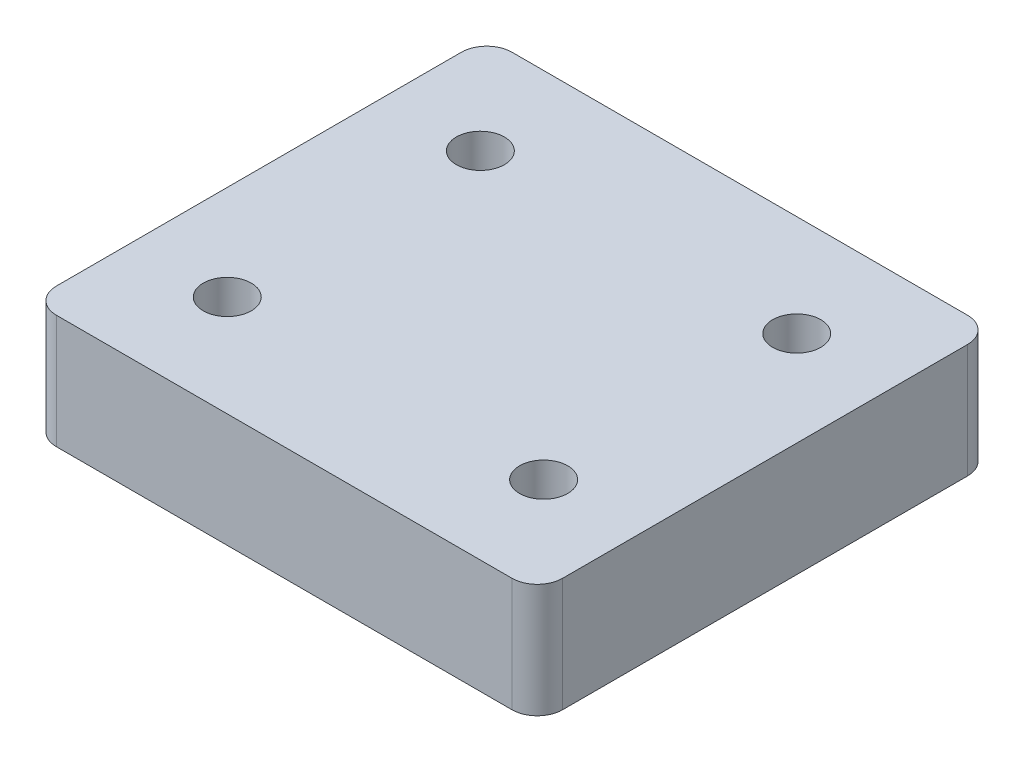
SolidWorks part; units mm, degrees
ref_plane "Front Plane" through (0, 0, 0) normal (0, 0, 1) x (1, 0, 0)
ref_plane "Top Plane" through (0, 0, 0) normal (0, 1, 0) x (1, 0, 0)
ref_plane "Right Plane" through (0, 0, 0) normal (1, 0, 0) x (0, 0, -1)
sketch "Sketch1" plane through (0, 0, 0) normal (0, 1, 0) x (1, 0, 0)
  line L1 (-10.5177, 16.6808) -> (29.4823, 16.6808)
  line L2 (-10.5177, 16.6808) -> (-10.5177, -19.3192)
  line L3 (-10.5177, -19.3192) -> (29.4823, -19.3192)
  line L4 (29.4823, 16.6808) -> (29.4823, -19.3192)
  dimension "D1" = 40
  dimension "D2" = 36
extrude "Boss-Extrude1" add sketch "Sketch1" along normal blind 9
sketch "Sketch2" plane through (0, 9, 0) normal (0, 1, 0) x (1, 0, 0)
  line L1 (-10.5177, -19.3192) -> (29.4823, -19.3192) construction
  line L2 (29.4823, 16.6808) -> (-10.5177, 16.6808) construction
  line L3 (29.4823, -19.3192) -> (29.4823, 16.6808) construction
  circle A0 centre (-3.0177, -11.3192) radius 1.9
  circle A1 centre (21.9823, -11.3192) radius 1.9
  circle A2 centre (-3.0177, 8.6808) radius 1.9
  circle A3 centre (21.9823, 8.6808) radius 1.9
  point P12 (0, 0)
  point P13 (0, 0)
  point P14 (0, 0)
  dimension "D1" = 25
  dimension "D3" = 8
  dimension "D6" = 7.5
  dimension "D2" = 8
  dimension "D4" = 25
  dimension "D5" = 20
extrude "Cut-Extrude1" cut sketch "Sketch2" against normal blind 10
fillet "Fillet1" radius 2 4 edges at (-10.5177, 4.5, -16.6808) (-10.5177, 4.5, 19.3192) (29.4823, 4.5, -16.6808) (29.4823, 4.5, 19.3192)
